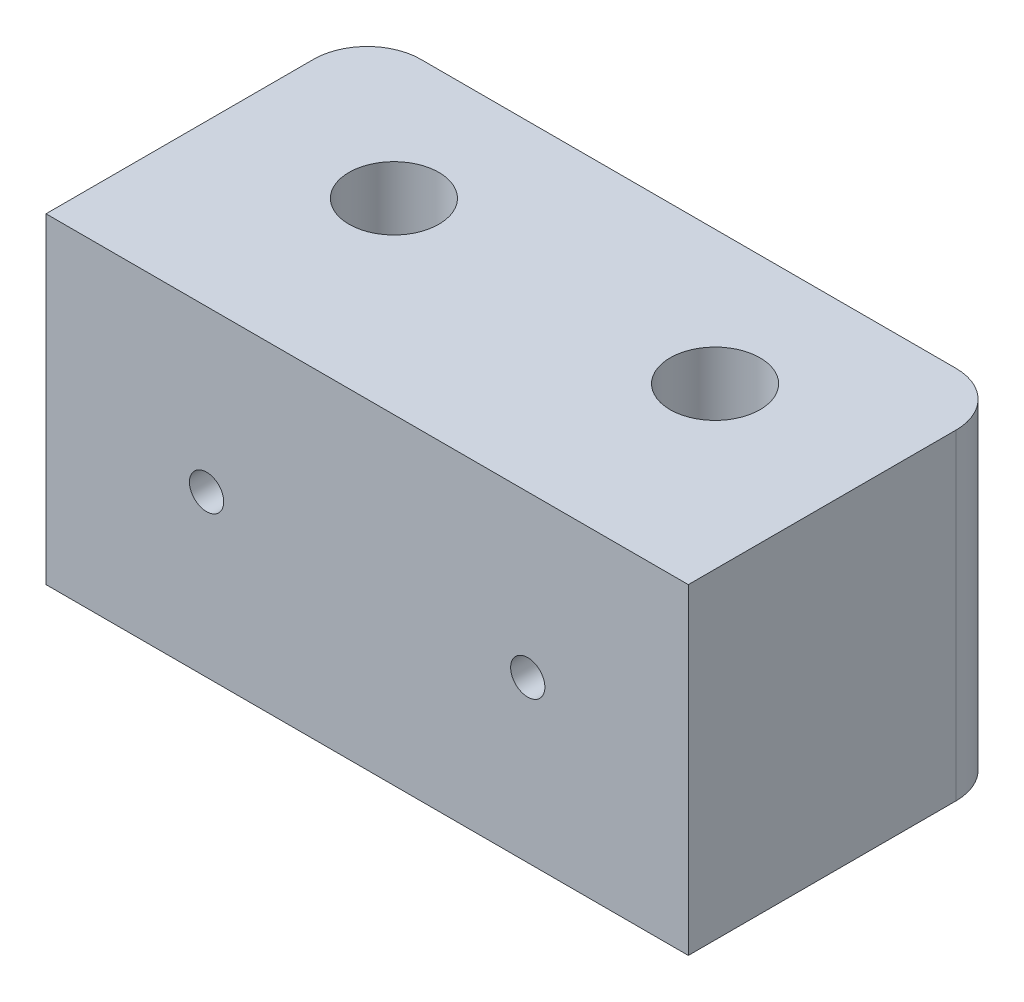
SolidWorks part; units mm, degrees
material "1060 Alloy"
ref_plane "Front Plane" through (0, 0, 0) normal (0, 0, 1) x (1, 0, 0)
ref_plane "Top Plane" through (0, 0, 0) normal (0, 1, 0) x (1, 0, 0)
ref_plane "Right Plane" through (0, 0, 0) normal (1, 0, 0) x (0, 0, -1)
sketch "Sketch1" plane through (0, 0, 0) normal (0, 1, 0) x (1, 0, 0)
  line L0 (-44.2539, 0) -> (44.2539, 0) construction
  line L1 (-15, 7.5) -> (15, 7.5)
  line L2 (-15, 7.5) -> (-15, -7.5)
  line L3 (-15, -7.5) -> (15, -7.5)
  line L4 (15, 7.5) -> (15, -7.5)
  line L5 (0, -44.7868) -> (0, 44.7868) construction
  point P4 (-15, 0)
  point P7 (0, 7.5)
  dimension "D1" = 30
  dimension "D2" = 15
extrude "Boss-Extrude1" add sketch "Sketch1" along normal blind 15
fillet "Fillet1" radius 2.5 2 edges at (-15, 7.5, -7.5) (15, 7.5, -7.5)
hole_wizard "M5 Tapped Hole1" positions "Sketch2" profile "Sketch3" tap size "M5" standard "ISO"
sketch "Sketch2" plane through (0, 15, 0) normal (0, 1, 0) x (1, 0, 0)
  line L0 (0, -44.7868) -> (0, 44.7868) construction
  line L2 (12.5, 7.5) -> (-12.5, 7.5) construction
  point P0 (-7.5, 1.25)
  point P2 (7.5, 1.25)
  dimension "D1" = 7.5
  dimension "D2" = 7.5
  dimension "D3" = 6.25
  dimension "D4" = 0
sketch "Sketch3" plane through (-7.5, 15, -1.25) normal (1, 0, 0) x (0, 0, 1)
  line L0 (0, 0) -> (0, 13.6618)
  line L1 (0, 13.6618) -> (2.1, 12.4)
  line L2 (2.1, 12.4) -> (2.1, 0)
  line L5 (2.1, 0) -> (0, 0)
  line L10 (0, 13.6618) -> (-2.1, 12.4) construction
  line L11 (0, -6.35) -> (0, 107.95) construction
  dimension "Tap Drill Dia." = 4.2
  dimension "Tap Drill Depth" = 12.4
  dimension "Drill Angle" = 118
hole_wizard "M2 Tapped Hole1" positions "Sketch4" profile "Sketch5" tap size "M2" standard "ISO"
sketch "Sketch4" plane through (0, 0, 7.5) normal (0, 0, 1) x (1, 0, 0)
  line L0 (-15, 15) -> (15, 15) construction
  line L2 (0, -44.7868) -> (0, 44.7868) construction
  point P0 (7.5, 7.5)
  point P2 (-7.5, 7.5)
  dimension "D1" = 7.5
  dimension "D2" = 7.5
  dimension "D3" = 7.5
sketch "Sketch5" plane through (7.5, 7.5, 7.5) normal (1, 0, 0) x (0, -1, 0)
  line L0 (0, 0) -> (0, 5.4807)
  line L1 (0, 5.4807) -> (0.8, 5)
  line L2 (0.8, 5) -> (0.8, 0)
  line L5 (0.8, 0) -> (0, 0)
  line L10 (0, 5.4807) -> (-0.8, 5) construction
  line L11 (0, -6.35) -> (0, 107.95) construction
  dimension "Tap Drill Dia." = 1.6
  dimension "Tap Drill Depth" = 5
  dimension "Drill Angle" = 118
cosmetic thread "Hole Thread1"
cosmetic thread "Hole Thread2"
